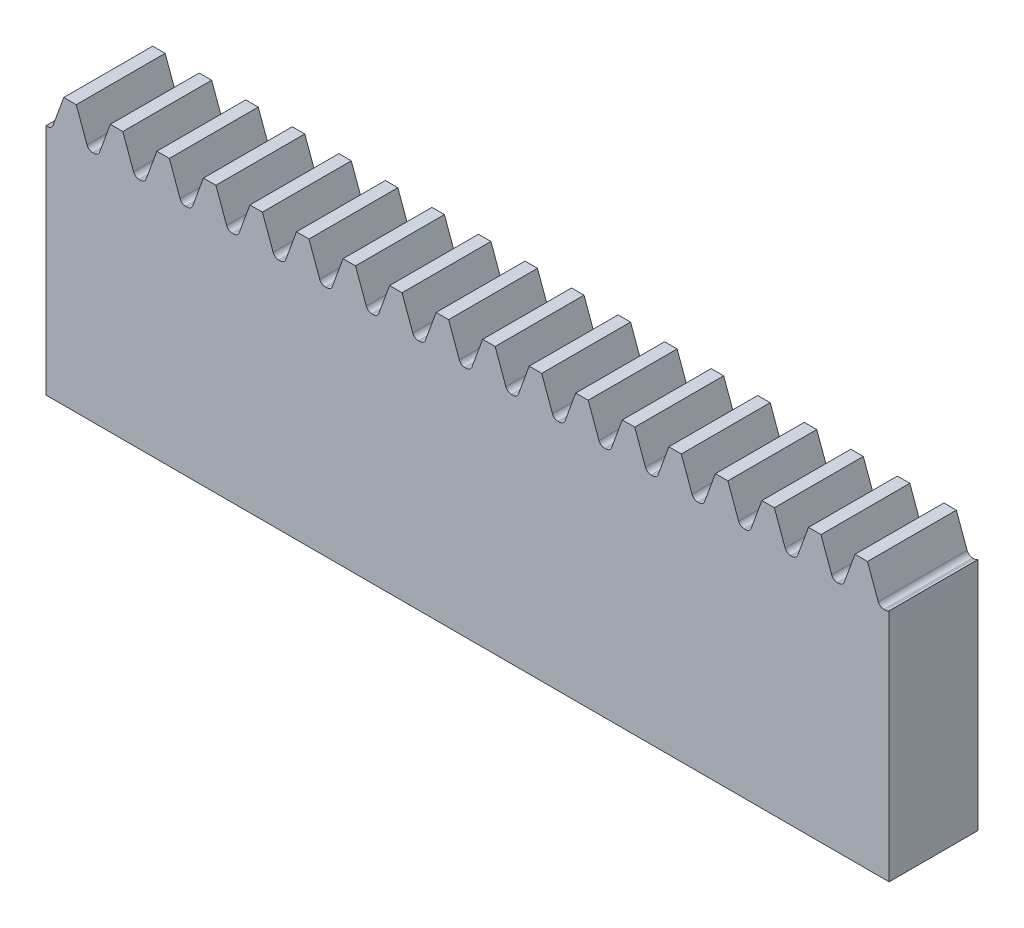
SolidWorks part; units mm, degrees
ref_plane "Front Plane" through (0, 0, 0) normal (0, 0, 1) x (1, 0, 0)
ref_plane "Top Plane" through (0, 0, 0) normal (0, 1, 0) x (1, 0, 0)
ref_plane "Right Plane" through (0, 0, 0) normal (1, 0, 0) x (0, 0, -1)
ref_plane "Dim.Module" through (0.5, 0, 0) normal (1, 0, 0) x (0, 0, -1)
sketch "Sketch1" plane through (0, 0, 0) normal (0, 0, 1) x (1, 0, 0)
  line L1 (0, 0) -> (30, 0)
  line L2 (0, 0) -> (0, 9)
  line L3 (0, 9) -> (30, 9)
  line L4 (30, 0) -> (30, 9)
  dimension "H" = 9
  dimension "L" = 30
extrude "Boss-Extrude1" add sketch "Sketch1" against normal mid plane 3
sketch "Sketch2" plane through (0, 0, 1.5) normal (0, 0, 1) x (1, 0, 0)
  line L0 (0, 0) -> (0, 9) construction
  line L1 (0, 9) -> (30, 9) construction
  line L2 (-0.5747, 9) -> (0.5747, 9)
  line L3 (0.5747, 9) -> (0.2131, 8.0066)
  line L4 (0.0252, 7.875) -> (-0.0252, 7.875)
  line L5 (30, 0) -> (30, 9) construction
  line L6 (-0.3927, 8.5) -> (30, 8.5) construction
  line L9 (-0.5747, 9) -> (-0.2131, 8.0066)
  arc A0 (0.2131, 8.0066) -> (0.0252, 7.875) centre (0.0252, 8.075) cw
  arc A1 (-0.2131, 8.0066) -> (-0.0252, 7.875) centre (-0.0252, 8.075) ccw
  dimension "D2" = 20
  dimension "H_s" = 8.5
  dimension "KSS_3" = 0.2
extrude "Cut-Extrude1" cut sketch "Sketch2" against normal through all
pattern_linear "LPattern1" count 20 spacing 1.5708 along (1, 0, 0) of "Cut-Extrude1"
ref_plane "Dim.MC" through (-3, 0, 0) normal (-1, 0, 0) x (0, 0, 1)
ref_plane "Dim.WMC" through (3, 0, 0) normal (1, 0, 0) x (0, 0, -1)
hole_wizard "Tap1" [suppressed] positions "Sketch4" profile "Sketch3" hole size "M3x0.5" standard "JIS"
sketch "Sketch4" [suppressed] plane through (0, 0, 0) normal (-1, 0, 0) x (0, 0, 1)
  line L2 (-5, 0) -> (5, 0) construction
  point P0 (0, 5.5)
sketch "Sketch3" [suppressed] plane through (0, 5.5, 0) normal (0, 1, 0) x (0, 0, 1)
  line L0 (0, 0) -> (0, 8.2388)
  line L1 (0, 8.2388) -> (1.2295, 7.5)
  line L2 (1.2295, 7.5) -> (1.2295, 0)
  line L5 (1.2295, 0) -> (0, 0)
  line L10 (0, 8.2388) -> (-1.2295, 7.5) construction
  line L11 (0, 0) -> (0, 8.2388) construction
  dimension "Drill Angle" = 118
  dimension "HSL_1" = 7.5
cosmetic thread "Thread1" [suppressed] parameters "MC"=3
hole_wizard "Tap2" [suppressed] positions "Sketch6" profile "Sketch5" hole size "M3x0.5" standard "JIS"
sketch "Sketch6" [suppressed] plane through (0, 0, 0) normal (-1, 0, 0) x (0, 0, 1)
  line L1 (-5, 0) -> (5, 0) construction
  line L6 (0, 0) -> (0, 12) construction
  point P0 (0, 5.5)
sketch "Sketch5" [suppressed] plane through (0, 5.5, 0) normal (0, 1, 0) x (0, 0, 1)
  line L0 (0, 0) -> (0, 8.2388)
  line L1 (0, 8.2388) -> (1.2295, 7.5)
  line L2 (1.2295, 7.5) -> (1.2295, 0)
  line L5 (1.2295, 0) -> (0, 0)
  line L10 (0, 8.2388) -> (-1.2295, 7.5) construction
  line L11 (0, 0) -> (0, 8.2388) construction
  dimension "Drill Angle" = 118
  dimension "HSL_2" = 7.5
cosmetic thread "Thread2" [suppressed]
hole_wizard "Tap3" [suppressed] positions "Sketch8" profile "Sketch7" hole size "M3x0.5" standard "JIS"
sketch "Sketch8" [suppressed] plane through (50, -0.0905, -0.628) normal (1, 0, 0) x (0, 0, -1)
  point P0 (-0.628, 5.5905)
sketch "Sketch7" [suppressed] plane through (50, 5.5, 0) normal (0, 1, 0) x (0, 0, -1)
  line L0 (0, 0) -> (0, 8.2388)
  line L1 (0, 8.2388) -> (1.2295, 7.5)
  line L2 (1.2295, 7.5) -> (1.2295, 0)
  line L5 (1.2295, 0) -> (0, 0)
  line L10 (0, 8.2388) -> (-1.2295, 7.5) construction
  line L11 (0, 0) -> (0, 8.2388) construction
  dimension "Drill Angle" = 118
  dimension "HSL_2" = 7.5
cosmetic thread "Thread3" [suppressed]
sketch "Sketch9" plane through (0, 9, 0) normal (0, 1, 0) x (1, 0, 0)
  line L4 (1.3577, -1.5) -> (1.5456, -1.5)
  line L5 (1.5456, -1.5) -> (1.5456, 1.5)
  line L6 (1.5456, 1.5) -> (1.3577, 1.5)
  line L7 (1.3577, 1.5) -> (1.3577, -1.5)
  line L8 (0, -1.5) -> (1.5456, -1.5)
  line L9 (1.5456, -1.5) -> (1.5456, 1.5)
  line L10 (1.5456, 1.5) -> (0, 1.5)
  line L11 (0, 1.5) -> (0, -1.5)
  dimension "D1" = 0
extrude "Cut-Extrude2" cut sketch "Sketch9" against normal through all
equation "\"Factor\"= 1.082532"
equation "\"H_s/2\"= \"H_s\" / 2"
equation "\"D2\"= INT ( ( \"L\" / ( \"Module\" * PI ) ) ) + 2"
equation "\"P\"= \"Module\" * PI"
equation "\"KSS_2\"= 1.25 * \"Module\""
equation "\"KSS_3\"= 0.4 * \"Module\""
equation "\"KSS_4\"= ( \"Module\" * PI ) / 2"
equation "\"MCx2\"= \"MC\" * 2"
equation "\"Pitch_MC\"= IIF ( \"MC\" = 30 , 3.5 , IIF ( \"MC\" = 27 , 3 , IIF ( \"MC\" = 24 , 3 , IIF ( \"MC\" = 22 , 2.5 , IIF ( \"MC\" = 20 , 2.5 , IIF ( \"MC\" = 18 , 2.5 , IIF ( \"MC\" = 16 , 2 , IIF ( \"MC\" = 12 , 1.75 , IIF ( \"MC\" = 10 , 1.5 , IIF ( \"MC\" = 8 , 1.25 , IIF ( \"MC\" = 6 , 1 , IIF ( \"MC\" = 5 , 0.8 , IIF ( \"MC\" = 4 , 0.7 , IIF ( \"MC\" = 3.5 , 0.6 , IIF ( \"MC\" = 3 , 0.5 , IIF ( \"MC\" = 2.6 , 0.45 , 0.4 ) ) ) ) ) ) ) ) ) ) ) ) ) ) ) )"
equation "\"HSD_1\"= round ( \"MC\" - \"Factor\" * \"Pitch_MC\" , 3 )"
equation "\"HSL_1\"= round ( \"MCx2\" + \"Pitch_MC\" * 3 , 1 )"
equation "\"WMCx2\"= \"WMC\" * 2"
equation "\"Pitch_WMC\"= IIF ( \"WMC\" = 30 , 3.5 , IIF ( \"WMC\" = 27 , 3 , IIF ( \"WMC\" = 24 , 3 , IIF ( \"WMC\" = 22 , 2.5 , IIF ( \"WMC\" = 20 , 2.5 , IIF ( \"WMC\" = 18 , 2.5 , IIF ( \"WMC\" = 16 , 2 , IIF ( \"WMC\" = 12 , 1.75 , IIF ( \"WMC\" = 10 , 1.5 , IIF ( \"WMC\" = 8 , 1.25 , IIF ( \"WMC\" = 6 , 1 , IIF ( \"WMC\" = 5 , 0.8 , IIF ( \"WMC\" = 4 , 0.7 , IIF ( \"WMC\" = 3.5 , 0.6 , IIF ( \"WMC\" = 3 , 0.5 , IIF ( \"WMC\" = 2.6 , 0.45 , 0.4 ) ) ) ) ) ) ) ) ) ) ) ) ) ) ) )"
equation "\"HSD_2\"= round ( \"WMC\" - \"Factor\" * \"Pitch_WMC\" , 3 )"
equation "\"HSL_2\"= round ( \"WMCx2\" + \"Pitch_WMC\" * 3 , 1 )"
